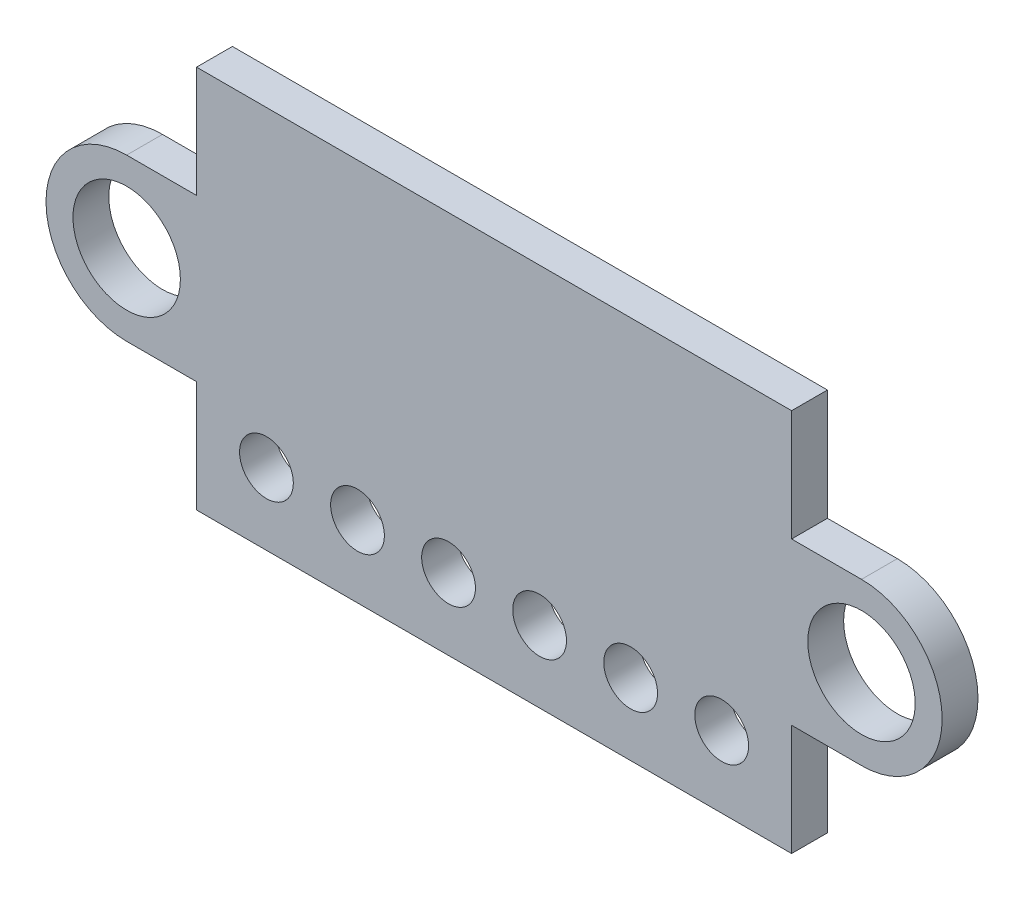
SolidWorks part; units mm, degrees
ref_plane "前视基准面" through (0, 0, 0) normal (0, 0, 1) x (1, 0, 0)
ref_plane "上视基准面" through (0, 0, 0) normal (0, 1, 0) x (1, 0, 0)
ref_plane "右视基准面" through (0, 0, 0) normal (1, 0, 0) x (0, 0, -1)
sketch "草图1" plane through (0, 0, 0) normal (0, 0, 1) x (1, 0, 0)
  line L0 (-10.25, 2.25) -> (-8.3, 2.25)
  line L1 (-8.3, 5.35) -> (8.3, 5.35)
  line L2 (-8.3, 5.35) -> (-8.3, 2.25)
  line L3 (-8.3, -5.35) -> (8.3, -5.35)
  line L4 (8.3, 5.35) -> (8.3, 2.25)
  line L5 (-8.3, 5.35) -> (8.3, -5.35) construction
  line L6 (-8.3, -5.35) -> (8.3, 5.35) construction
  line L7 (-10.25, -2.25) -> (-8.3, -2.25)
  line L8 (0, 13.9527) -> (0, -18.5918) construction
  line L9 (10.25, -2.25) -> (8.3, -2.25)
  line L10 (10.25, 2.25) -> (8.3, 2.25)
  line L11 (-31.292, 0) -> (34.3861, 0) construction
  line L12 (-13.6449, -3.35) -> (10.8, -3.35) construction
  line L13 (8.3, -2.25) -> (8.3, -5.35)
  line L14 (-8.3, -2.25) -> (-8.3, -5.35)
  arc A0 (-10.25, 2.25) -> (-10.25, -2.25) centre (-10.25, 0) ccw
  arc A1 (10.25, 2.25) -> (10.25, -2.25) centre (10.25, 0) cw
  circle A2 centre (-10.25, 0) radius 1.4983
  circle A3 centre (10.25, 0) radius 1.4983
  circle A4 centre (-6.35, -3.35) radius 0.75
  circle A5 centre (-3.81, -3.35) radius 0.75
  circle A6 centre (-1.27, -3.35) radius 0.75
  circle A7 centre (1.27, -3.35) radius 0.75
  circle A8 centre (3.81, -3.35) radius 0.75
  circle A9 centre (6.35, -3.35) radius 0.75
  point P0 (0, 0)
  dimension "D3" = 4.5
  dimension "D5" = 2.9966
  dimension "D6" = 2
  dimension "D7" = 6
  dimension "D10" = 1.27
  dimension "D8" = 1.5
  dimension "D11" = 16.6
  dimension "D2" = 10.7
  dimension "D4" = 1.95
  dimension "D9" = 1.27
extrude "凸台-拉伸1" add sketch "草图1" along normal blind 1
sketch "草图3" plane through (0, 0, 0) normal (0, 0, -1) x (-1, 0, 0)
  line L0 (-8.3, 5.35) -> (8.3, 5.35) construction
  line L1 (-1.228, 1.2498) -> (0.6588, 1.2498)
  line L2 (-1.228, 1.2498) -> (-1.228, -0.9088)
  line L3 (-1.228, -0.9088) -> (0.6588, -0.9088)
  line L4 (0.6588, 1.2498) -> (0.6588, -0.9088)
  line L5 (-1.228, 1.2498) -> (0.6588, -0.9088) construction
  line L6 (-1.228, -0.9088) -> (0.6588, 1.2498) construction
  line L7 (3.8852, 2.4054) -> (6.2432, 2.4054)
  line L8 (3.8852, 2.4054) -> (3.8852, 0.6758)
  line L9 (3.8852, 0.6758) -> (6.2432, 0.6758)
  line L10 (6.2432, 2.4054) -> (6.2432, 0.6758)
  line L11 (3.8852, 2.4054) -> (6.2432, 0.6758) construction
  line L12 (3.8852, 0.6758) -> (6.2432, 2.4054) construction
  line L13 (-8.3, 2.25) -> (-8.3, 5.35) construction
  line L14 (8.3, 5.35) -> (8.3, 2.25) construction
  point P0 (5.0642, 1.5406)
  point P10 (-0.2846, 0.1705)
  dimension "D1" = 1.8868
  dimension "D2" = 2.1586
  dimension "D3" = 5.1795
  dimension "D4" = 8.0154
  dimension "D5" = 2.358
  dimension "D6" = 1.7296
  dimension "D7" = 3.2358
  dimension "D8" = 4.6742
extrude "凸台-拉伸2" add sketch "草图3" along normal blind 1
